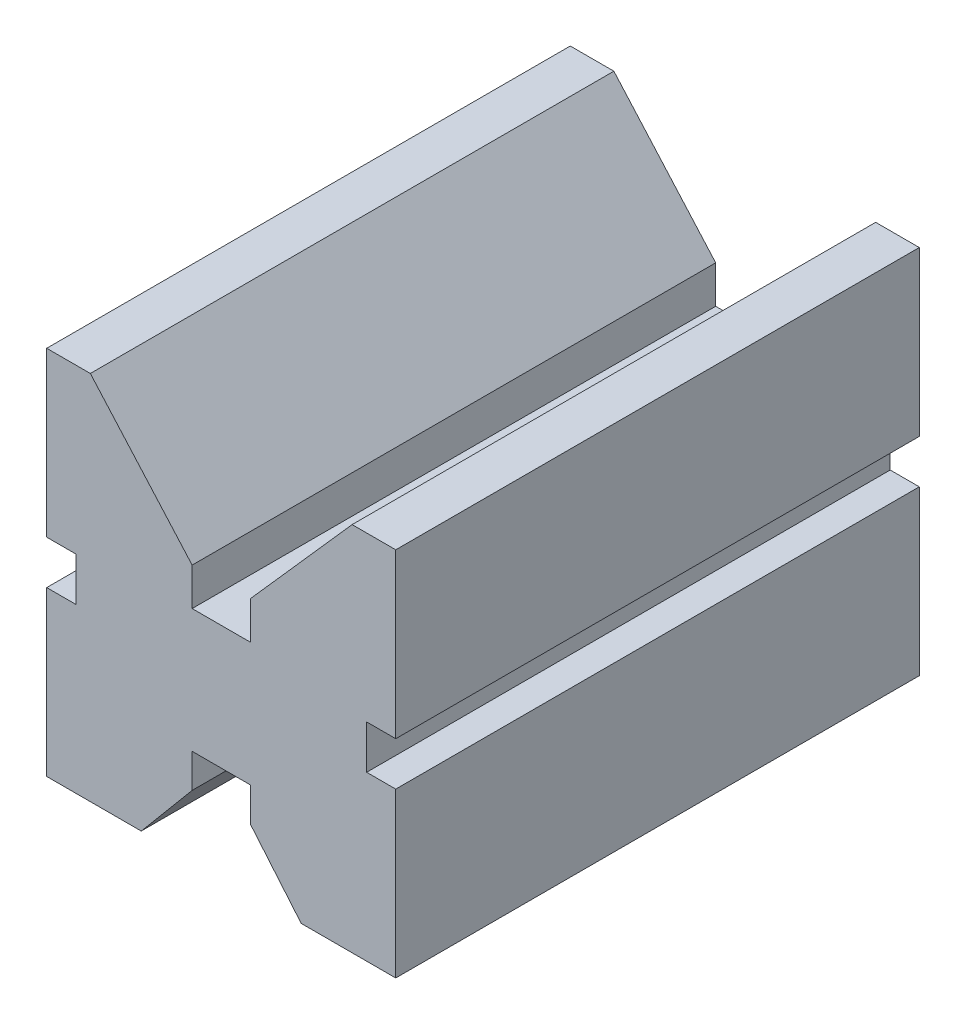
SolidWorks part; units mm, degrees
ref_plane "Front Plane" through (0, 0, 0) normal (0, 0, 1) x (1, 0, 0)
ref_plane "Top Plane" through (0, 0, 0) normal (0, 1, 0) x (1, 0, 0)
ref_plane "Right Plane" through (0, 0, 0) normal (1, 0, 0) x (0, 0, -1)
sketch "Sketch1" plane through (0, 0, 0) normal (0, 0, 1) x (1, 0, 0)
  line L0 (0, 0) -> (39.9298, 0) construction
  line L1 (-24, 25.5) -> (-4, 25.5)
  line L2 (-24, 25.5) -> (-24, 3)
  line L3 (-24, -25.5) -> (-4, -25.5)
  line L4 (24, 25.5) -> (24, 3)
  line L5 (-24, 25.5) -> (24, -25.5) construction
  line L6 (-24, -25.5) -> (24, 25.5) construction
  line L7 (24, 3) -> (20, 3)
  line L9 (24, -3) -> (20, -3)
  line L10 (20, 3) -> (20, -3)
  line L11 (0, -55) -> (0, 55) construction
  line L12 (-24, 3) -> (-20, 3)
  line L13 (-24, -3) -> (-20, -3)
  line L14 (-20, 3) -> (-20, -3)
  line L15 (0, 0) -> (0, 30.3316) construction
  line L17 (-4, 25.5) -> (-4, 4.5)
  line L18 (-4, 4.5) -> (4, 4.5)
  line L19 (4, 25.5) -> (4, 4.5)
  line L20 (4, 25.5) -> (24, 25.5)
  line L21 (4, -25.5) -> (4, -12.5)
  line L22 (-4, -25.5) -> (-4, -12.5)
  line L23 (-4, -12.5) -> (4, -12.5)
  line L24 (4, -25.5) -> (24, -25.5)
  line L25 (-24, -3) -> (-24, -25.5)
  line L26 (24, -3) -> (24, -25.5)
  point P0 (0, 0)
  dimension "D1" = 48
  dimension "D2" = 51
  dimension "D3" = 6
  dimension "D4" = 4
  dimension "D5" = 21
  dimension "D6" = 8
  dimension "D7" = 13
  dimension "D8" = 8
extrude "Boss-Extrude1" add sketch "Sketch1" along normal mid plane 72
sketch "Sketch3" plane through (0, 0, 36) normal (0, 0, 1) x (1, 0, 0)
  line L0 (-4, 9.6759) -> (-18, 25.5)
  line L1 (-4, 4.5) -> (-4, 25.5) construction
  line L2 (-4, 25.5) -> (-24, 25.5) construction
  line L3 (-4, 25.5) -> (-18, 25.5)
  line L4 (-4, 9.6759) -> (-4, 25.5)
  line L5 (0, 0) -> (0, 16.7898) construction
  line L6 (4, 9.6759) -> (18, 25.5)
  line L7 (24, 25.5) -> (4, 25.5) construction
  line L8 (4, 25.5) -> (4, 4.5) construction
  line L9 (18, 25.5) -> (4, 25.5)
  line L10 (4, 25.5) -> (4, 9.6759)
  line L11 (4, -17.1577) -> (11, -25.5)
  line L12 (4, -12.5) -> (4, -25.5) construction
  line L13 (4, -25.5) -> (24, -25.5) construction
  line L14 (-4, -17.1577) -> (-11, -25.5)
  line L15 (24, -25.5) -> (24, -3) construction
  line L16 (-4, -25.5) -> (-4, -12.5) construction
  line L17 (-24, -25.5) -> (-4, -25.5) construction
  line L18 (4, -25.5) -> (11, -25.5)
  line L19 (4, -17.1577) -> (4, -25.5)
  line L20 (-4, -25.5) -> (-4, -17.1577)
  line L21 (-11, -25.5) -> (-4, -25.5)
  dimension "D1" = 83
  dimension "D2" = 6
  dimension "D3" = 80
  dimension "D4" = 13
extrude "Cut-Extrude1" cut sketch "Sketch3" against normal through all
